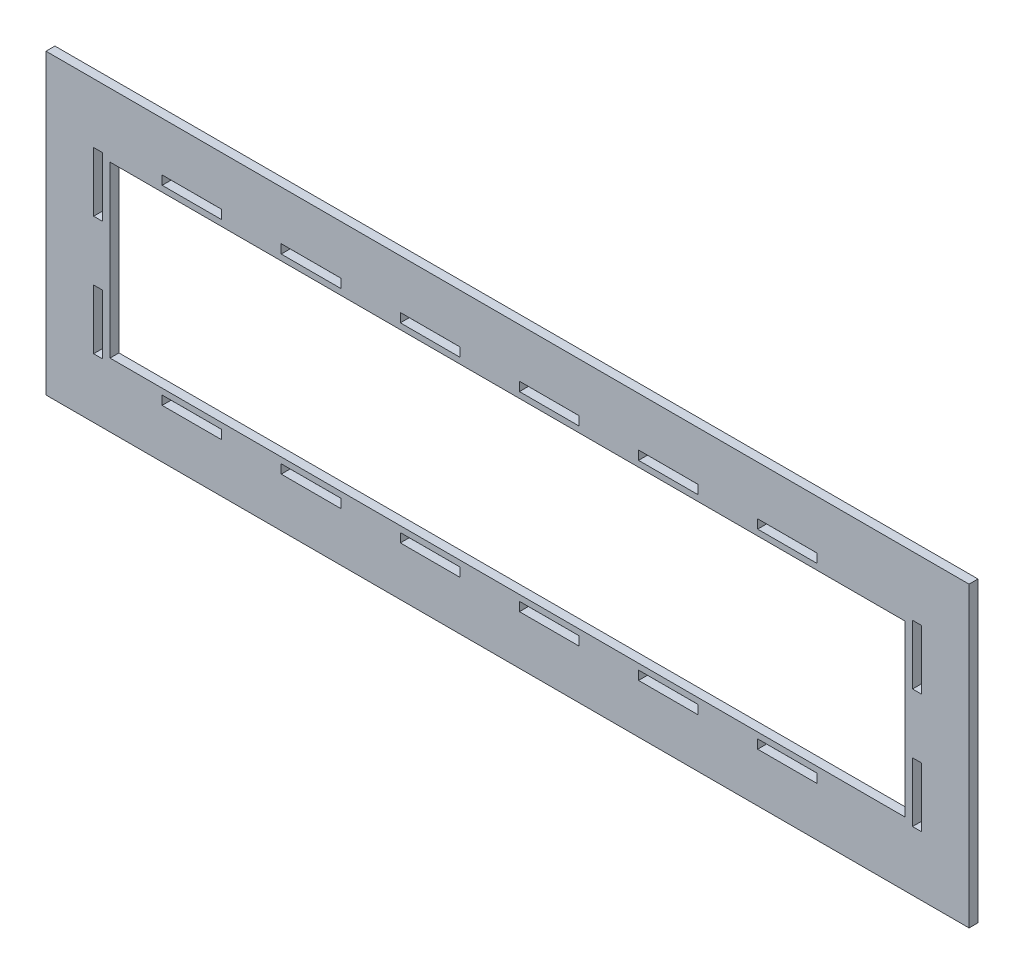
SolidWorks part; units mm, degrees
ref_plane "Alzado" through (0, 0, 0) normal (0, 0, 1) x (1, 0, 0)
ref_plane "Planta" through (0, 0, 0) normal (0, 1, 0) x (1, 0, 0)
ref_plane "Vista lateral" through (0, 0, 0) normal (1, 0, 0) x (0, 0, -1)
sketch "Croquis1" plane through (0, 0, 0) normal (0, 0, 1) x (1, 0, 0)
  line L1 (-310, 100) -> (310, 100)
  line L2 (-310, 100) -> (-310, -100)
  line L3 (-310, -100) -> (310, -100)
  line L4 (310, 100) -> (310, -100)
  line L5 (-310, 100) -> (310, -100) construction
  line L6 (-310, -100) -> (310, 100) construction
  line L7 (267, 57) -> (-267, 57)
  line L8 (267, 57) -> (267, -57)
  line L9 (267, -57) -> (-267, -57)
  line L10 (-267, 57) -> (-267, -57)
  line L11 (267, 57) -> (-267, -57) construction
  line L12 (267, -57) -> (-267, 57) construction
  point P0 (0, 0)
  point P6 (0, 0)
  dimension "D1" = 620
  dimension "D2" = 200
  dimension "D3" = 534
  dimension "D4" = 114
extrude "Saliente-Extruir1" add sketch "Croquis1" along normal blind 6
sketch "Croquis2" plane through (0, 0, 6) normal (0, 0, 1) x (1, 0, 0)
  line L0 (-267, 57) -> (-267, -57) construction
  line L1 (-278.02, 60) -> (-272, 60) construction
  line L2 (-278.02, 60) -> (-278.02, -60) construction
  line L3 (-278.02, -60) -> (-272, -60) construction
  line L4 (-272, 60) -> (-272, -60) construction
  line L5 (-278.02, 60) -> (-272, -60) construction
  line L6 (-278.02, -60) -> (-272, 60) construction
  line L7 (0, 126.1217) -> (0, -145.5943) construction
  line L8 (278.02, -60) -> (272, -60) construction
  line L9 (-278.02, 60) -> (-272, 60)
  line L10 (-278.02, 60) -> (-278.02, 20)
  line L11 (-278.02, 20) -> (-272, 20)
  line L12 (-272, 60) -> (-272, 20)
  line L13 (-278.02, -60) -> (-272, -60)
  line L14 (-278.02, -60) -> (-278.02, -20)
  line L15 (-278.02, -20) -> (-272, -20)
  line L16 (-272, -60) -> (-272, -20)
  line L17 (272, -60) -> (272, -20)
  line L18 (278.02, -20) -> (272, -20)
  line L19 (278.02, -60) -> (278.02, -20)
  line L20 (278.02, -60) -> (272, -60)
  line L21 (278.02, 60) -> (272, 60) construction
  line L22 (272, 60) -> (272, 20)
  line L23 (278.02, 20) -> (272, 20)
  line L24 (278.02, 60) -> (278.02, 20)
  line L25 (278.02, 60) -> (272, 60)
  line L26 (-67.9607, 0) -> (71.0745, 0) construction
  point P0 (-275.01, 0)
  point P8 (-267, 0)
  dimension "D1" = 6.02
  dimension "D2" = 120
  dimension "D3" = 5
  dimension "D4" = 40
  dimension "D5" = 40
extrude "Cortar-Extruir1" cut sketch "Croquis2" against normal blind 6
sketch "Croquis3" plane through (0, 0, 6) normal (0, 0, 1) x (1, 0, 0)
  line L1 (-232, 67.02) -> (-192, 67.02)
  line L2 (-232, 67.02) -> (-232, 61)
  line L3 (-232, 61) -> (-192, 61)
  line L4 (-192, 67.02) -> (-192, 61)
  line L5 (-272, 20) -> (-272, 60) construction
  dimension "D1" = 6.02
  dimension "D2" = 40
  dimension "D3" = 61
  dimension "D4" = 40
extrude "Cortar-Extruir2" cut sketch "Croquis3" against normal blind 6
pattern_linear "MatrizL1" count 6 spacing 80 along (1, 0, 0) of "Cortar-Extruir2"
mirror "Simetría1" about plane through (0, 0, 0) normal (0, 1, 0) of "MatrizL1", "Cortar-Extruir2"
